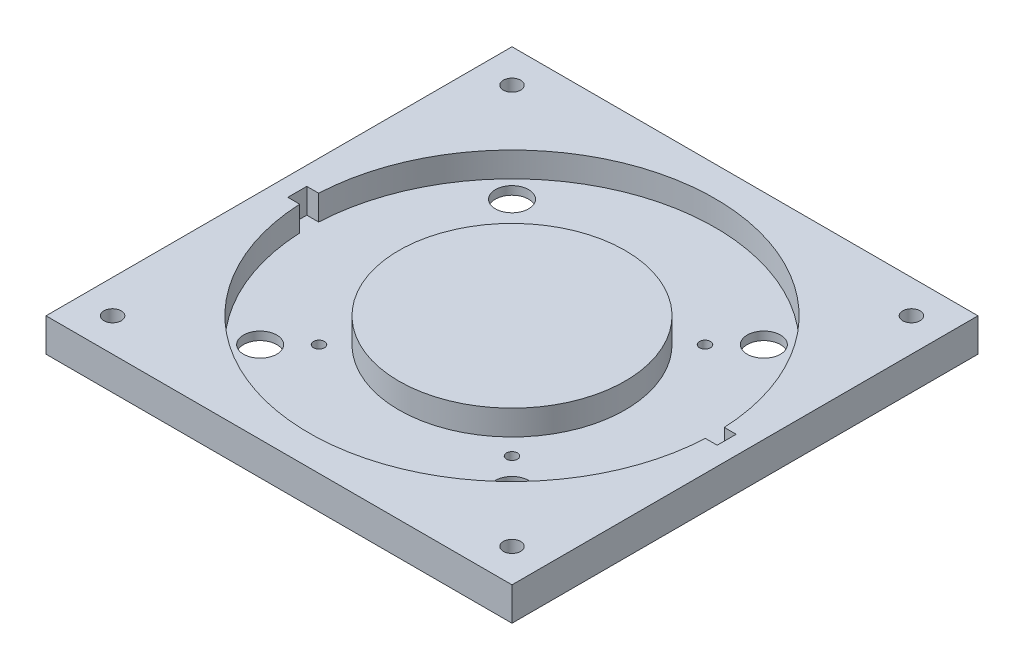
SolidWorks part; units mm, degrees
ref_plane "前视基准面" through (0, 0, 0) normal (0, 0, 1) x (1, 0, 0)
ref_plane "上视基准面" through (0, 0, 0) normal (0, 1, 0) x (1, 0, 0)
ref_plane "右视基准面" through (0, 0, 0) normal (1, 0, 0) x (0, 0, -1)
sketch "草图1" plane through (0, 0, 0) normal (0, 1, 0) x (1, 0, 0)
  line L1 (-70, -70) -> (70, -70)
  line L2 (-70, -70) -> (-70, 70)
  line L3 (-70, 70) -> (70, 70)
  line L4 (70, -70) -> (70, 70)
  line L5 (-70, -70) -> (70, 70) construction
  line L6 (-70, 70) -> (70, -70) construction
  circle A0 centre (0, 0) radius 41 construction
  circle A1 centre (0, 0) radius 53.5 construction
  circle A2 centre (-37.8302, 37.8302) radius 5
  circle A3 centre (-28.9914, 28.9914) radius 1.65
  circle A4 centre (28.9914, 28.9914) radius 1.65
  circle A5 centre (37.8302, 37.8302) radius 5
  circle A6 centre (28.9914, -28.9914) radius 1.65
  circle A7 centre (37.8302, -37.8302) radius 5
  circle A8 centre (-28.9914, -28.9914) radius 1.65
  circle A9 centre (-37.8302, -37.8302) radius 5
  point P0 (0, 0)
  point P28 (0, 0)
  dimension "D3" = 107
  dimension "D4" = 82
  dimension "D5" = 3.3
  dimension "D7" = 10
  dimension "D1" = 140
  dimension "D2" = 140
  dimension "D6" = 4
extrude "凸台-拉伸1" add sketch "草图1" along normal blind 10
sketch "草图2" plane through (0, 10, 0) normal (0, 1, 0) x (1, 0, 0)
  line L0 (70, 70) -> (-70, 70) construction
  line L1 (-60, 60) -> (60, 60) construction
  line L2 (-60, 60) -> (-60, -60) construction
  line L3 (-60, -60) -> (60, -60) construction
  line L4 (60, 60) -> (60, -60) construction
  line L5 (-60, 60) -> (60, -60) construction
  line L6 (-60, -60) -> (60, 60) construction
  line L7 (70, -70) -> (70, 70) construction
  circle A0 centre (-60, 60) radius 2.6
  circle A1 centre (60, 60) radius 2.6
  circle A2 centre (60, -60) radius 2.6
  circle A3 centre (-60, -60) radius 2.6
  circle A5 centre (0, 0) radius 60 construction
  point P0 (0, 0)
  point P20 (0, 0)
  dimension "D3" = 5.2
  dimension "D5" = 120
  dimension "D1" = 10
  dimension "D2" = 10
  dimension "D4" = 4
extrude "切除-拉伸1" cut sketch "草图2" against normal through all
sketch "草图3" plane through (0, 10, 0) normal (0, 1, 0) x (1, 0, 0)
  circle A0 centre (0, 0) radius 61
  circle A1 centre (0, 0) radius 46
  dimension "D1" = 122
  dimension "D2" = 92
extrude "切除-拉伸2" cut sketch "草图3" against normal blind 7.5
sketch "草图4" plane through (0, 10, 0) normal (0, 1, 0) x (1, 0, 0)
  circle A0 centre (0, 0) radius 46 construction
  circle A1 centre (0, 0) radius 46
  circle A2 centre (0, 0) radius 34
  dimension "D1" = 68
extrude "切除-拉伸3" cut sketch "草图4" against normal blind 7.5
sketch "草图5" plane through (0, 10, 0) normal (0, 1, 0) x (1, 0, 0)
  line L0 (-70, 0) -> (70, 0) construction
  line L1 (-70, 70) -> (-70, -70) construction
  line L2 (70, -70) -> (70, 70) construction
  line L3 (0, 70) -> (0, -70) construction
  line L4 (-64.5, 2.85) -> (-57.5, 2.85)
  line L5 (-64.5, 2.85) -> (-64.5, -2.85)
  line L6 (-64.5, -2.85) -> (-57.5, -2.85)
  line L7 (-57.5, 2.85) -> (-57.5, -2.85)
  line L8 (-64.5, 2.85) -> (-57.5, -2.85) construction
  line L9 (-64.5, -2.85) -> (-57.5, 2.85) construction
  line L10 (70, 70) -> (-70, 70) construction
  line L11 (-70, -70) -> (70, -70) construction
  line L12 (64.5, -2.85) -> (57.5, -2.85)
  line L13 (57.5, 2.85) -> (57.5, -2.85)
  line L14 (64.5, 2.85) -> (57.5, 2.85)
  line L15 (64.5, 2.85) -> (64.5, -2.85)
  circle A0 centre (0, 0) radius 61 construction
  point P6 (-61, 0)
  dimension "D1" = 5.7
  dimension "D2" = 3.5
extrude "切除-拉伸4" cut sketch "草图5" against normal up to surface (7.5 mm away) up to face at (-37.8302, 2.5, -32.8302)
sketch "草图6" plane through (0, 10, 0) normal (0, 1, 0) x (1, 0, 0)
  circle A0 centre (-60, 60) radius 5
  circle A1 centre (60, 60) radius 5
  circle A2 centre (-60, -60) radius 5
  circle A3 centre (60, -60) radius 5
  dimension "D1" = 10
extrude "切除-拉伸5" [suppressed] cut sketch "草图6" against normal blind 6
